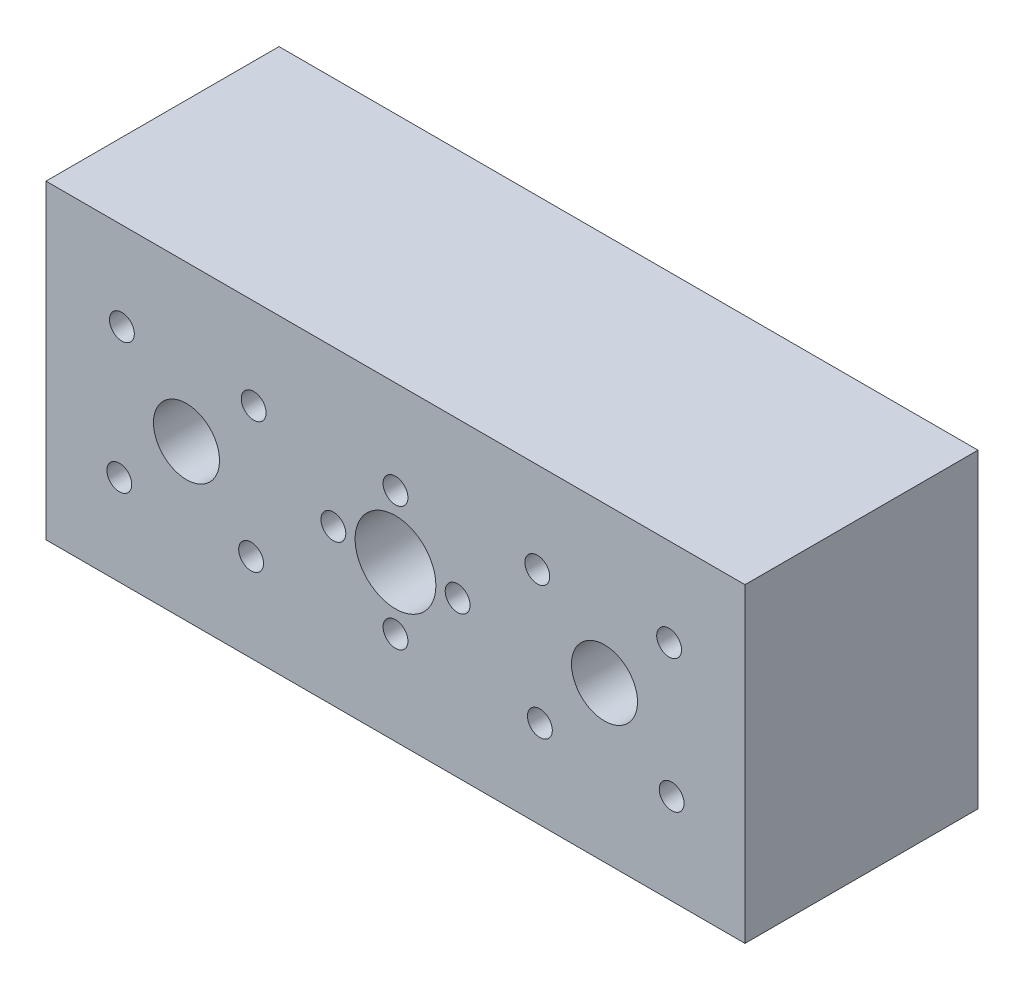
SolidWorks part; units mm, degrees
ref_plane "前视基准面" through (0, 0, 0) normal (0, 0, 1) x (1, 0, 0)
ref_plane "上视基准面" through (0, 0, 0) normal (0, 1, 0) x (1, 0, 0)
ref_plane "右视基准面" through (0, 0, 0) normal (1, 0, 0) x (0, 0, -1)
other "Configuration Table"
sketch "草图1" plane through (0, 0, 0) normal (0, 0, 1) x (1, 0, 0)
  line L1 (-45, -20) -> (45, -20)
  line L2 (-45, -20) -> (-45, 20)
  line L3 (-45, 20) -> (45, 20)
  line L4 (45, -20) -> (45, 20)
  line L5 (-45, -20) -> (45, 20) construction
  line L6 (-45, 20) -> (45, -20) construction
  point P0 (0, 0)
  dimension "D1" = 90
  dimension "D2" = 40
extrude "凸台-拉伸1" add sketch "草图1" along normal blind 30
hole_wizard "丝杆孔" positions "草图2" profile "草图3" legacy end condition through all
sketch "草图2" plane through (0, 0, 30) normal (0, 0, 1) x (1, 0, 0)
  point P0 (0, 0)
sketch "草图3" plane through (0, 0, 30) normal (1, 0, 0) x (0, -1, 0)
  line L0 (0, 0) -> (0, 30)
  line L1 (0, 30) -> (4.25, 30)
  line L2 (4.25, 30) -> (4.25, 0)
  line L3 (4.25, 0) -> (0, 0)
  line L4 (0, 110) -> (0, -10) construction
  dimension "直径" = 8.5
  dimension "深度" = 30
hole_wizard "丝杆座孔" positions "草图5" profile "草图6" legacy
sketch "草图5" plane through (0, 0, 30) normal (0, 0, 1) x (1, 0, 0)
  point P0 (0, 0)
sketch "草图6" plane through (0, 0, 30) normal (1, 0, 0) x (0, -1, 0)
  line L0 (0, 0) -> (0, 12)
  line L1 (0, 12) -> (5.2, 12)
  line L2 (5.2, 12) -> (5.2, 0)
  line L3 (5.2, 0) -> (0, 0)
  line L4 (0, 110) -> (0, -10) construction
  dimension "直径" = 10.4
  dimension "深度" = 12
hole_wizard "丝杆螺丝孔" positions "草图7" profile "草图8" legacy end condition through all
sketch "草图7" plane through (0, 0, 30) normal (0, 0, 1) x (1, 0, 0)
  point P0 (8, 0)
  point P3 (0, 8)
  point P6 (-8, 0)
  point P9 (0, -8)
sketch "草图8" plane through (8, 0, 30) normal (1, 0, 0) x (0, -1, 0)
  line L0 (0, 0) -> (0, 30)
  line L1 (0, 30) -> (1.6, 30)
  line L2 (1.6, 30) -> (1.6, 0)
  line L3 (1.6, 0) -> (0, 0)
  line L4 (0, 110) -> (0, -10) construction
  dimension "直径" = 3.2
  dimension "深度" = 30
hole_wizard "光轴孔" positions "草图11" profile "草图12" legacy end condition through all
sketch "草图11" plane through (0, 0, 0) normal (0, 0, -1) x (-1, 0, 0)
  line L0 (-200000, 0) -> (200045, 0) construction
  point P0 (-26.9092, 0)
sketch "草图12" plane through (26.9092, 0, 0) normal (1, 0, 0) x (0, 1, 0)
  line L0 (0, 0) -> (0, 30)
  line L1 (0, 30) -> (4.25, 30)
  line L2 (4.25, 30) -> (4.25, 0)
  line L3 (4.25, 0) -> (0, 0)
  line L4 (0, 110) -> (0, -10) construction
  dimension "直径" = 8.5
  dimension "深度" = 30
hole_wizard "光轴座螺丝孔" positions "草图13" profile "草图14" legacy end condition through all
sketch "草图13" plane through (0, 0, 0) normal (0, 0, -1) x (-1, 0, 0)
  point P0 (-18.2612, 8.3193)
  point P3 (-35.2286, 8.648)
  point P6 (-35.5572, -8.3193)
  point P9 (-18.5899, -8.648)
sketch "草图14" plane through (18.2612, 8.3193, 0) normal (1, 0, 0) x (0, 1, 0)
  line L0 (0, 0) -> (0, 30)
  line L1 (0, 30) -> (1.6, 30)
  line L2 (1.6, 30) -> (1.6, 0)
  line L3 (1.6, 0) -> (0, 0)
  line L4 (0, 110) -> (0, -10) construction
  dimension "直径" = 3.2
  dimension "深度" = 30
hole_wizard "光轴座孔" positions "草图15" profile "草图16" legacy
sketch "草图15" plane through (0, 0, 0) normal (0, 0, -1) x (-1, 0, 0)
  point P0 (-26.9092, 0)
sketch "草图16" plane through (26.9092, 0, 0) normal (1, 0, 0) x (0, 1, 0)
  line L0 (0, 0) -> (0, 20)
  line L1 (0, 20) -> (8.5, 20)
  line L2 (8.5, 20) -> (8.5, 0)
  line L3 (8.5, 0) -> (0, 0)
  line L4 (0, 110) -> (0, -10) construction
  dimension "直径" = 17
  dimension "深度" = 20
ref_plane "基准面1" through (0, 0, 0) normal (-1, 0, 0) x (0, 0, 1)
mirror "镜向1" about plane through (0, 0, 0) normal (-1, 0, 0) of "光轴座螺丝孔", "光轴孔", "光轴座孔"
